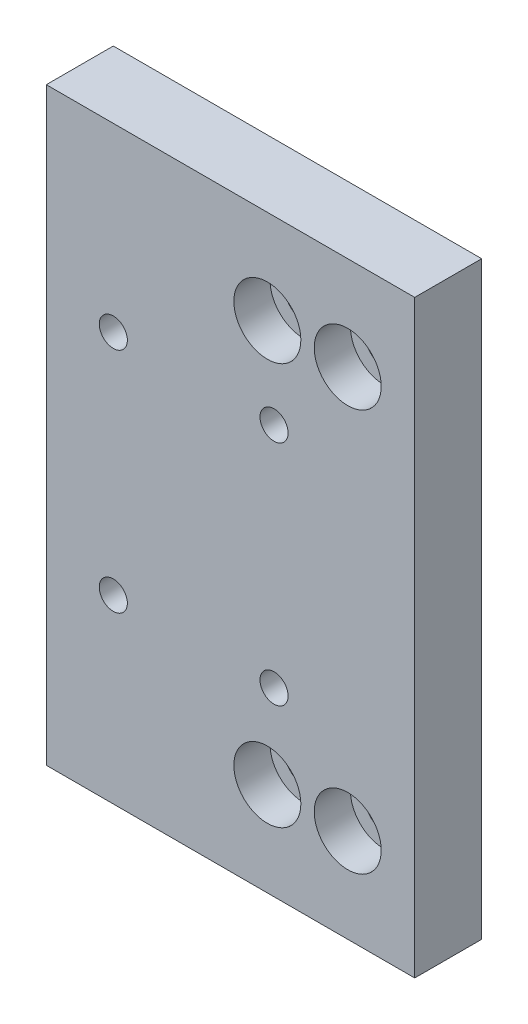
SolidWorks part; units mm, degrees
ref_plane "Front Plane" through (0, 0, 0) normal (0, 0, 1) x (1, 0, 0)
ref_plane "Top Plane" through (0, 0, 0) normal (0, 1, 0) x (1, 0, 0)
ref_plane "Right Plane" through (0, 0, 0) normal (1, 0, 0) x (0, 0, -1)
sketch "Sketch1" plane through (0, 0, 0) normal (0, 0, 1) x (1, 0, 0)
  line L1 (-27.5, 44) -> (27.5, 44)
  line L2 (-27.5, 44) -> (-27.5, -44)
  line L3 (-27.5, -44) -> (27.5, -44)
  line L4 (27.5, 44) -> (27.5, -44)
  line L5 (-27.5, 44) -> (27.5, -44) construction
  line L6 (-27.5, -44) -> (27.5, 44) construction
  point P0 (0, 0)
  dimension "D1" = 55
  dimension "D2" = 88
extrude "Boss-Extrude1" add sketch "Sketch1" along normal blind 10
hole_wizard "M5 Tapped Hole1" positions "Sketch2" profile "Sketch4" tap size "M5" standard "ISO" end condition through all
sketch "Sketch2" plane through (0, 0, 10) normal (0, 0, 1) x (1, 0, 0)
  line L1 (27.5, -44) -> (27.5, 44) construction
  point P0 (-17.5, 17)
  point P2 (6.5, 17)
  point P5 (-17.5, -17)
  point P7 (6.5, -17)
  dimension "D1" = 24
  dimension "D2" = 34
  dimension "D3" = 17
  dimension "D4" = 21
sketch "Sketch4" plane through (-17.5, 17, 10) normal (1, 0, 0) x (0, -1, 0)
  line L0 (0, 0) -> (0, 10)
  line L1 (0, 10) -> (2.1, 10)
  line L2 (2.1, 10) -> (2.1, 0)
  line L5 (2.1, 0) -> (0, 0)
  line L11 (0, -6.35) -> (0, 107.95) construction
  dimension "Thru Tap Drill Dia." = 4.2
  dimension "Thru Tap Drill Depth" = 10
cosmetic thread "Hole Thread1"
cosmetic thread "Hole Thread2"
cosmetic thread "Hole Thread3"
cosmetic thread "Hole Thread4"
hole_wizard "CBORE for M5 Hex Socket Head Cap Screw1" positions "Sketch5" profile "Sketch6" counterbore size "M5" standard "ISO" end condition through all
sketch "Sketch5" plane through (0, 0, 10) normal (0, 0, 1) x (1, 0, 0)
  line L0 (27.5, -44) -> (27.5, 44) construction
  point P0 (5.5, 30)
  point P2 (17.5, 30)
  point P4 (17.5, -30)
  point P6 (5.5, -30)
  dimension "D1" = 12
  dimension "D2" = 10
  dimension "D3" = 60
  dimension "D4" = 30
sketch "Sketch6" plane through (5.5, 30, 10) normal (1, 0, 0) x (0, -1, 0)
  line L0 (0, 0) -> (0, 10)
  line L1 (0, 10) -> (2.75, 10)
  line L3 (2.75, 10) -> (2.75, 5.4)
  line L4 (2.75, 5.4) -> (5, 5.4)
  line L5 (5, 5.4) -> (5, 0)
  line L7 (5, 0) -> (0, 0)
  line L11 (0, -6.35) -> (0, 107.95) construction
  dimension "Thru Hole Dia." = 5.5
  dimension "Thru Hole Depth" = 10
  dimension "C'Bore Dia." = 10
  dimension "C'Bore Depth" = 5.4
